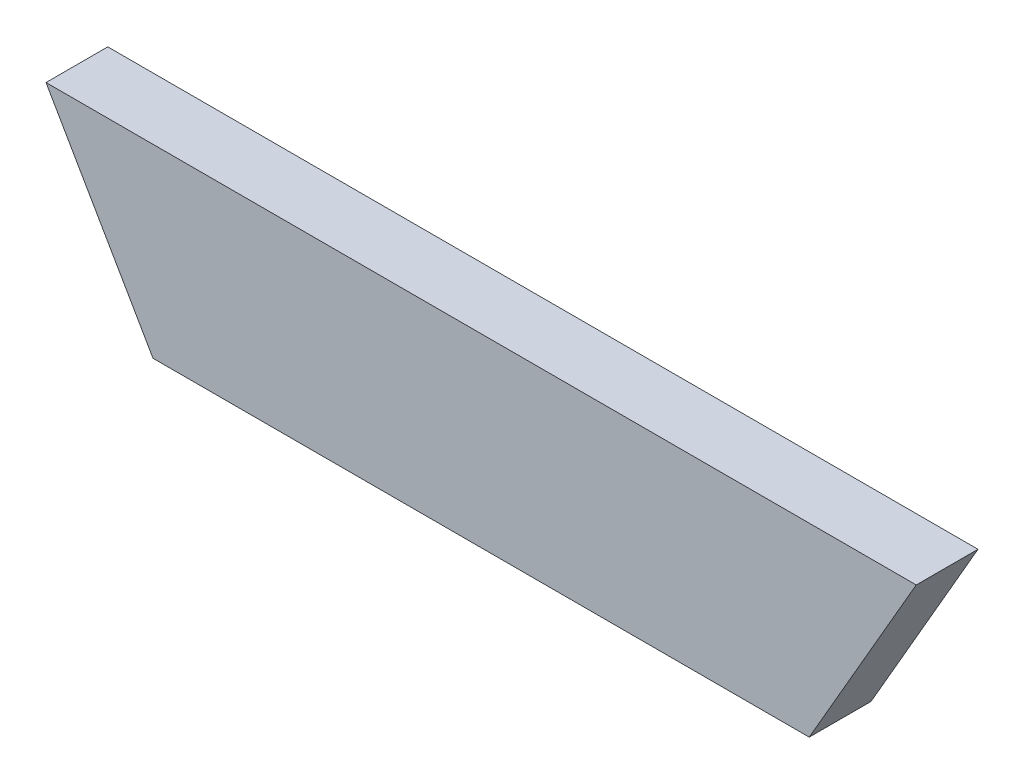
SolidWorks part; units mm, degrees
ref_plane "Plan de face" through (0, 0, 0) normal (0, 0, 1) x (1, 0, 0)
ref_plane "Plan de dessus" through (0, 0, 0) normal (0, 1, 0) x (1, 0, 0)
ref_plane "Plan de droite" through (0, 0, 0) normal (1, 0, 0) x (0, 0, -1)
sketch "Esquisse1" plane through (0, 0, 0) normal (0, 0, 1) x (1, 0, 0)
  line L0 (-225.0031, 84.1096) -> (-13.6831, 84.1096)
  line L1 (-13.6831, 84.1096) -> (-39.6638, 39.1096)
  line L2 (-39.6638, 39.1096) -> (-199.0223, 39.1096)
  line L3 (-199.0223, 39.1096) -> (-225.0031, 84.1096)
  dimension "D1" = 211.32
  dimension "D2" = 120
  dimension "D3" = 45
extrude "Boss.-Extru.1" add sketch "Esquisse1" along normal blind 15
